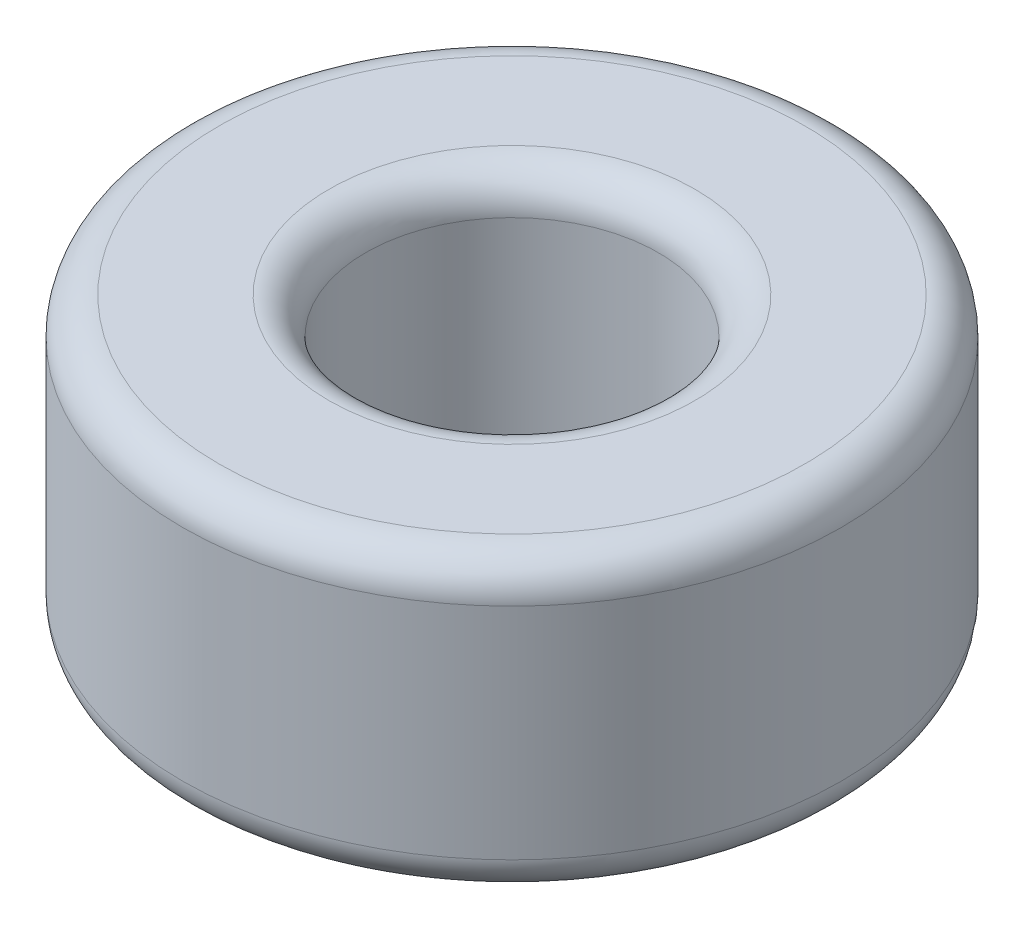
SolidWorks part; units mm, degrees
material "球墨鑄鐵"
ref_plane "前基準面" through (0, 0, 0) normal (0, 0, 1) x (1, 0, 0)
ref_plane "上基準面" through (0, 0, 0) normal (0, 1, 0) x (1, 0, 0)
ref_plane "右基準面" through (0, 0, 0) normal (1, 0, 0) x (0, 0, -1)
sketch "草圖1" plane through (0, 0, 0) normal (0, 1, 0) x (1, 0, 0)
  circle A0 centre (0, 0) radius 4.5
  circle A1 centre (0, 0) radius 2
  dimension "D1" = 9
  dimension "D2" = 4
extrude "填料-伸長1" add sketch "草圖1" along normal blind 4
fillet "圓角1" radius 0.5 4 edges at (0, 0, 2) (0, 0, 4.5) (0, 4, 2) (0, 4, 4.5)
